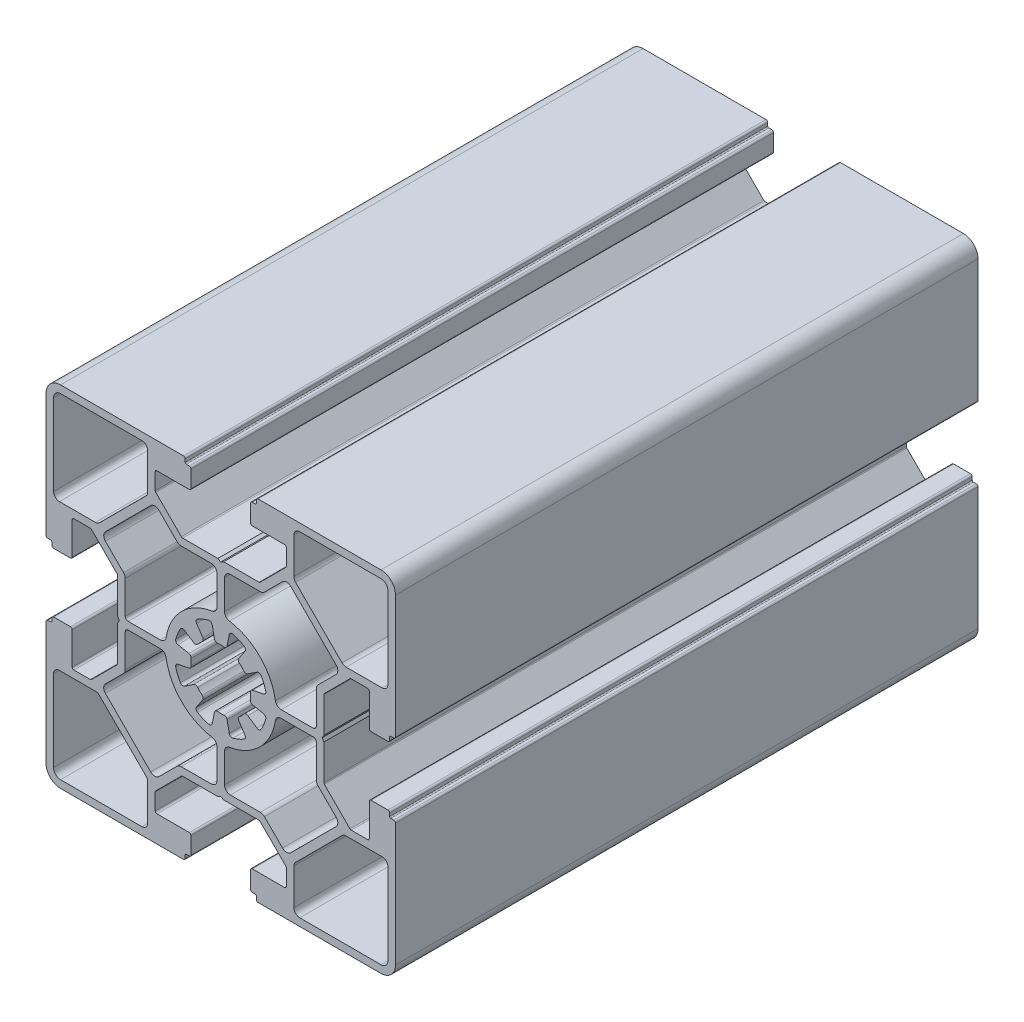
SolidWorks part; units mm, degrees
ref_plane "前视基准面" through (0, 0, 0) normal (0, 0, 1) x (1, 0, 0)
ref_plane "上视基准面" through (0, 0, 0) normal (0, 1, 0) x (1, 0, 0)
ref_plane "右视基准面" through (0, 0, 0) normal (1, 0, 0) x (0, 0, -1)
sketch "草图1" plane through (0, 0, 0) normal (0, 0, 1) x (1, 0, 0)
  line B0 (17.7, -0.4992) -> (17.4113, 0.0008)
  line B1 (17.4113, 0.0008) -> (17.7, 0.5008)
  line B2 (17.7, 0.5008) -> (17.7, 6.5449)
  line B3 (17.7879, 6.757) -> (22.193, 11.1621)
  line B4 (22.4051, 11.25) -> (25.2, 11.25)
  line B5 (25.5, 10.95) -> (25.5, 5.4)
  line B6 (25.8, 5.1) -> (28.7, 5.1)
  line B7 (29, 5.4) -> (29, 5.9)
  line B8 (29.2, 6.1) -> (29.7, 6.1)
  line B9 (30, 6.4) -> (30, 27.5)
  line B10 (27.5, 30) -> (6.4, 30)
  line B11 (6.1, 29.7) -> (6.1, 29.2)
  line B12 (5.9, 29) -> (5.4, 29)
  line B13 (5.1, 28.7) -> (5.1, 25.8)
  line B14 (5.4, 25.5) -> (10.95, 25.5)
  line B15 (11.25, 25.2) -> (11.25, 22.4051)
  line B16 (11.1621, 22.193) -> (6.757, 17.7879)
  line B17 (6.5449, 17.7) -> (0.5, 17.7)
  line B18 (0.5, 17.7) -> (0, 17.4113)
  line B19 (0, 17.4113) -> (-0.5, 17.7)
  line B20 (-0.5, 17.7) -> (-6.5449, 17.7)
  line B21 (-6.757, 17.7879) -> (-11.1621, 22.193)
  line B22 (-11.25, 22.4051) -> (-11.25, 25.2)
  line B23 (-10.95, 25.5) -> (-5.4, 25.5)
  line B24 (-5.1, 25.8) -> (-5.1, 28.7)
  line B25 (-5.4, 29) -> (-5.9, 29)
  line B26 (-6.1, 29.2) -> (-6.1, 29.7)
  line B27 (-6.4, 30) -> (-27.5, 30)
  line B28 (-30, 27.5) -> (-30, 6.4)
  line B29 (-29.7, 6.1) -> (-29.2, 6.1)
  line B30 (-29, 5.9) -> (-29, 5.4)
  line B31 (-28.7, 5.1) -> (-25.8, 5.1)
  line B32 (-25.5, 5.4) -> (-25.5, 10.95)
  line B33 (-25.2, 11.25) -> (-22.4051, 11.25)
  line B34 (-22.193, 11.1621) -> (-17.7879, 6.757)
  line B35 (-17.7, 6.5449) -> (-17.7, 0.5008)
  line B36 (-17.7, 0.5008) -> (-17.4113, 0.0008)
  line B37 (-17.4113, 0.0008) -> (-17.7, -0.4992)
  line B38 (-17.7, -0.4992) -> (-17.7, -6.5449)
  line B39 (-17.7879, -6.757) -> (-22.193, -11.1621)
  line B40 (-22.4051, -11.25) -> (-25.2, -11.25)
  line B41 (-25.5, -10.95) -> (-25.5, -5.4)
  line B42 (-25.8, -5.1) -> (-28.7, -5.1)
  line B43 (-29, -5.4) -> (-29, -5.9)
  line B44 (-29.2, -6.1) -> (-29.7, -6.1)
  line B45 (-30, -6.4) -> (-30, -27.5)
  line B46 (-27.5, -30) -> (-6.4, -30)
  line B47 (-6.1, -29.7) -> (-6.1, -29.2)
  line B48 (-5.9, -29) -> (-5.4, -29)
  line B49 (-5.1, -28.7) -> (-5.1, -25.8)
  line B50 (-5.4, -25.5) -> (-10.95, -25.5)
  line B51 (-11.25, -25.2) -> (-11.25, -22.4051)
  line B52 (-11.1621, -22.193) -> (-6.757, -17.7879)
  line B53 (-6.5449, -17.7) -> (-0.5, -17.7)
  line B54 (-0.5, -17.7) -> (0, -17.4113)
  line B55 (0, -17.4113) -> (0.5, -17.7)
  line B56 (0.5, -17.7) -> (6.5449, -17.7)
  line B57 (6.757, -17.7879) -> (11.1621, -22.193)
  line B58 (11.25, -22.4051) -> (11.25, -25.2)
  line B59 (10.95, -25.5) -> (5.4, -25.5)
  line B60 (5.1, -25.8) -> (5.1, -28.7)
  line B61 (5.4, -29) -> (5.9, -29)
  line B62 (6.1, -29.2) -> (6.1, -29.7)
  line B63 (6.4, -30) -> (27.5, -30)
  line B64 (30, -27.5) -> (30, -6.4)
  line B65 (29.7, -6.1) -> (29.2, -6.1)
  line B66 (29, -5.9) -> (29, -5.4)
  line B67 (28.7, -5.1) -> (25.8, -5.1)
  line B68 (25.5, -5.4) -> (25.5, -10.95)
  line B69 (25.2, -11.25) -> (22.4051, -11.25)
  line B70 (22.193, -11.1621) -> (17.7879, -6.757)
  line B71 (17.7, -6.5449) -> (17.7, -0.4992)
  line B72 (-16.4, 1.15) -> (-16.4, 6.7934)
  line B73 (-16.6929, 7.5005) -> (-19.799, 10.6066)
  line B74 (-19.799, 12.0208) -> (-12.0208, 19.799)
  line B75 (-10.6066, 19.799) -> (-7.5005, 16.6929)
  line B76 (-6.7934, 16.4) -> (-1.65, 16.4)
  line B77 (-0.65, 15.4) -> (-0.65, 10.3695)
  line B78 (-10.3695, 0.65) -> (-15.9, 0.65)
  line B79 (21.5225, 12.55) -> (27.7, 12.55)
  line B80 (28.7, 13.55) -> (28.7, 27.5)
  line B81 (27.5, 28.7) -> (13.55, 28.7)
  line B82 (12.55, 27.7) -> (12.55, 21.5225)
  line B83 (12.8429, 20.8154) -> (20.8154, 12.8429)
  line B84 (16.4, 6.7934) -> (16.4, 1.15)
  line B85 (15.9, 0.65) -> (10.3695, 0.65)
  line B86 (0.65, 10.3695) -> (0.65, 15.4)
  line B87 (1.65, 16.4) -> (6.7934, 16.4)
  line B88 (7.5005, 16.6929) -> (10.6066, 19.799)
  line B89 (12.0208, 19.799) -> (19.799, 12.0208)
  line B90 (19.799, 10.6066) -> (16.6929, 7.5005)
  line B91 (16.4, -1.15) -> (16.4, -6.7934)
  line B92 (16.6929, -7.5005) -> (19.799, -10.6066)
  line B93 (19.799, -12.0208) -> (12.0208, -19.799)
  line B94 (10.6066, -19.799) -> (7.5005, -16.6929)
  line B95 (6.7934, -16.4) -> (1.65, -16.4)
  line B96 (0.65, -15.4) -> (0.65, -10.3695)
  line B97 (10.3695, -0.65) -> (15.9, -0.65)
  line B98 (4.1575, -6.2221) -> (3.0988, -4.6376)
  line B99 (4.6376, -3.0988) -> (6.2221, -4.1575)
  line B100 (7.3395, -1.4599) -> (5.4705, -1.0881)
  line B101 (5.4705, 1.0881) -> (7.3395, 1.4599)
  line B102 (6.2221, 4.1575) -> (4.6376, 3.0988)
  line B103 (3.0988, 4.6376) -> (4.1575, 6.2221)
  line B104 (1.4599, 7.3395) -> (1.0881, 5.4705)
  line B105 (-1.0881, 5.4705) -> (-1.4599, 7.3395)
  line B106 (-4.1575, 6.2221) -> (-3.0988, 4.6376)
  line B107 (-4.6376, 3.0988) -> (-6.2221, 4.1575)
  line B108 (-7.3395, 1.4599) -> (-5.4705, 1.0881)
  line B109 (-5.4705, -1.0881) -> (-7.3395, -1.4599)
  line B110 (-6.2221, -4.1575) -> (-4.6376, -3.0988)
  line B111 (-3.0988, -4.6376) -> (-4.1575, -6.2221)
  line B112 (-1.4599, -7.3395) -> (-1.0881, -5.4705)
  line B113 (1.0881, -5.4705) -> (1.4599, -7.3395)
  line B114 (-21.5225, -12.55) -> (-27.7, -12.55)
  line B115 (-28.7, -13.55) -> (-28.7, -27.5)
  line B116 (-27.5, -28.7) -> (-13.55, -28.7)
  line B117 (-12.55, -27.7) -> (-12.55, -21.5225)
  line B118 (-12.8429, -20.8154) -> (-20.8154, -12.8429)
  line B119 (-16.4, -6.7934) -> (-16.4, -1.15)
  line B120 (-15.9, -0.65) -> (-10.3695, -0.65)
  line B121 (-0.65, -10.3695) -> (-0.65, -15.4)
  line B122 (-1.65, -16.4) -> (-6.7934, -16.4)
  line B123 (-7.5005, -16.6929) -> (-10.6066, -19.799)
  line B124 (-12.0208, -19.799) -> (-19.799, -12.0208)
  line B125 (-19.799, -10.6066) -> (-16.6929, -7.5005)
  line B126 (-20.8154, 12.8429) -> (-12.8429, 20.8154)
  line B127 (-12.55, 21.5225) -> (-12.55, 27.7)
  line B128 (-13.55, 28.7) -> (-27.5, 28.7)
  line B129 (-28.7, 27.5) -> (-28.7, 13.55)
  line B130 (-27.7, 12.55) -> (-21.5225, 12.55)
  line B131 (20.8154, -12.8429) -> (12.8429, -20.8154)
  line B132 (12.55, -21.5225) -> (12.55, -27.7)
  line B133 (13.55, -28.7) -> (27.5, -28.7)
  line B134 (28.7, -27.5) -> (28.7, -13.55)
  line B135 (27.7, -12.55) -> (21.5225, -12.55)
  arc B136 (17.7879, 6.757) -> (17.7, 6.5449) centre (18, 6.5449) ccw
  arc B137 (22.4051, 11.25) -> (22.193, 11.1621) centre (22.4051, 10.95) ccw
  arc B138 (25.5, 10.95) -> (25.2, 11.25) centre (25.2, 10.95) ccw
  arc B139 (25.5, 5.4) -> (25.8, 5.1) centre (25.8, 5.4) ccw
  arc B140 (28.7, 5.1) -> (29, 5.4) centre (28.7, 5.4) ccw
  arc B141 (29.2, 6.1) -> (29, 5.9) centre (29.2, 5.9) ccw
  arc B142 (29.7, 6.1) -> (30, 6.4) centre (29.7, 6.4) ccw
  arc B143 (30, 27.5) -> (27.5, 30) centre (27.5, 27.5) ccw
  arc B144 (6.4, 30) -> (6.1, 29.7) centre (6.4, 29.7) ccw
  arc B145 (5.9, 29) -> (6.1, 29.2) centre (5.9, 29.2) ccw
  arc B146 (5.4, 29) -> (5.1, 28.7) centre (5.4, 28.7) ccw
  arc B147 (5.1, 25.8) -> (5.4, 25.5) centre (5.4, 25.8) ccw
  arc B148 (11.25, 25.2) -> (10.95, 25.5) centre (10.95, 25.2) ccw
  arc B149 (11.1621, 22.193) -> (11.25, 22.4051) centre (10.95, 22.4051) ccw
  arc B150 (6.5449, 17.7) -> (6.757, 17.7879) centre (6.5449, 18) ccw
  arc B151 (-6.757, 17.7879) -> (-6.5449, 17.7) centre (-6.5449, 18) ccw
  arc B152 (-11.25, 22.4051) -> (-11.1621, 22.193) centre (-10.95, 22.4051) ccw
  arc B153 (-10.95, 25.5) -> (-11.25, 25.2) centre (-10.95, 25.2) ccw
  arc B154 (-5.4, 25.5) -> (-5.1, 25.8) centre (-5.4, 25.8) ccw
  arc B155 (-5.1, 28.7) -> (-5.4, 29) centre (-5.4, 28.7) ccw
  arc B156 (-6.1, 29.2) -> (-5.9, 29) centre (-5.9, 29.2) ccw
  arc B157 (-6.1, 29.7) -> (-6.4, 30) centre (-6.4, 29.7) ccw
  arc B158 (-27.5, 30) -> (-30, 27.5) centre (-27.5, 27.5) ccw
  arc B159 (-30, 6.4) -> (-29.7, 6.1) centre (-29.7, 6.4) ccw
  arc B160 (-29, 5.9) -> (-29.2, 6.1) centre (-29.2, 5.9) ccw
  arc B161 (-29, 5.4) -> (-28.7, 5.1) centre (-28.7, 5.4) ccw
  arc B162 (-25.8, 5.1) -> (-25.5, 5.4) centre (-25.8, 5.4) ccw
  arc B163 (-25.2, 11.25) -> (-25.5, 10.95) centre (-25.2, 10.95) ccw
  arc B164 (-22.193, 11.1621) -> (-22.4051, 11.25) centre (-22.4051, 10.95) ccw
  arc B165 (-17.7, 6.5449) -> (-17.7879, 6.757) centre (-18, 6.5449) ccw
  arc B166 (-17.7879, -6.757) -> (-17.7, -6.5449) centre (-18, -6.5449) ccw
  arc B167 (-22.4051, -11.25) -> (-22.193, -11.1621) centre (-22.4051, -10.95) ccw
  arc B168 (-25.5, -10.95) -> (-25.2, -11.25) centre (-25.2, -10.95) ccw
  arc B169 (-25.5, -5.4) -> (-25.8, -5.1) centre (-25.8, -5.4) ccw
  arc B170 (-28.7, -5.1) -> (-29, -5.4) centre (-28.7, -5.4) ccw
  arc B171 (-29.2, -6.1) -> (-29, -5.9) centre (-29.2, -5.9) ccw
  arc B172 (-29.7, -6.1) -> (-30, -6.4) centre (-29.7, -6.4) ccw
  arc B173 (-30, -27.5) -> (-27.5, -30) centre (-27.5, -27.5) ccw
  arc B174 (-6.4, -30) -> (-6.1, -29.7) centre (-6.4, -29.7) ccw
  arc B175 (-5.9, -29) -> (-6.1, -29.2) centre (-5.9, -29.2) ccw
  arc B176 (-5.4, -29) -> (-5.1, -28.7) centre (-5.4, -28.7) ccw
  arc B177 (-5.1, -25.8) -> (-5.4, -25.5) centre (-5.4, -25.8) ccw
  arc B178 (-11.25, -25.2) -> (-10.95, -25.5) centre (-10.95, -25.2) ccw
  arc B179 (-11.1621, -22.193) -> (-11.25, -22.4051) centre (-10.95, -22.4051) ccw
  arc B180 (-6.5449, -17.7) -> (-6.757, -17.7879) centre (-6.5449, -18) ccw
  arc B181 (6.757, -17.7879) -> (6.5449, -17.7) centre (6.5449, -18) ccw
  arc B182 (11.25, -22.4051) -> (11.1621, -22.193) centre (10.95, -22.4051) ccw
  arc B183 (10.95, -25.5) -> (11.25, -25.2) centre (10.95, -25.2) ccw
  arc B184 (5.4, -25.5) -> (5.1, -25.8) centre (5.4, -25.8) ccw
  arc B185 (5.1, -28.7) -> (5.4, -29) centre (5.4, -28.7) ccw
  arc B186 (6.1, -29.2) -> (5.9, -29) centre (5.9, -29.2) ccw
  arc B187 (6.1, -29.7) -> (6.4, -30) centre (6.4, -29.7) ccw
  arc B188 (27.5, -30) -> (30, -27.5) centre (27.5, -27.5) ccw
  arc B189 (30, -6.4) -> (29.7, -6.1) centre (29.7, -6.4) ccw
  arc B190 (29, -5.9) -> (29.2, -6.1) centre (29.2, -5.9) ccw
  arc B191 (29, -5.4) -> (28.7, -5.1) centre (28.7, -5.4) ccw
  arc B192 (25.8, -5.1) -> (25.5, -5.4) centre (25.8, -5.4) ccw
  arc B193 (25.2, -11.25) -> (25.5, -10.95) centre (25.2, -10.95) ccw
  arc B194 (22.193, -11.1621) -> (22.4051, -11.25) centre (22.4051, -10.95) ccw
  arc B195 (17.7, -6.5449) -> (17.7879, -6.757) centre (18, -6.5449) ccw
  arc B196 (-16.4, 6.7934) -> (-16.6929, 7.5005) centre (-17.4, 6.7934) ccw
  arc B197 (-19.799, 12.0208) -> (-19.799, 10.6066) centre (-19.0919, 11.3137) ccw
  arc B198 (-10.6066, 19.799) -> (-12.0208, 19.799) centre (-11.3137, 19.0919) ccw
  arc B199 (-7.5005, 16.6929) -> (-6.7934, 16.4) centre (-6.7934, 17.4) ccw
  arc B200 (-0.65, 15.4) -> (-1.65, 16.4) centre (-1.65, 15.4) ccw
  arc B201 (-1.4929, 9.382) -> (-0.65, 10.3695) centre (-1.65, 10.3695) ccw
  arc B202 (-1.4929, 9.382) -> (-9.382, 1.4929) centre (0, 0) ccw
  arc B203 (-10.3695, 0.65) -> (-9.382, 1.4929) centre (-10.3695, 1.65) ccw
  arc B204 (-16.4, 1.15) -> (-15.9, 0.65) centre (-15.9, 1.15) ccw
  arc B205 (20.8154, 12.8429) -> (21.5225, 12.55) centre (21.5225, 13.55) ccw
  arc B206 (27.7, 12.55) -> (28.7, 13.55) centre (27.7, 13.55) ccw
  arc B207 (28.7, 27.5) -> (27.5, 28.7) centre (27.5, 27.5) ccw
  arc B208 (13.55, 28.7) -> (12.55, 27.7) centre (13.55, 27.7) ccw
  arc B209 (12.55, 21.5225) -> (12.8429, 20.8154) centre (13.55, 21.5225) ccw
  arc B210 (15.9, 0.65) -> (16.4, 1.15) centre (15.9, 1.15) ccw
  arc B211 (9.382, 1.4929) -> (10.3695, 0.65) centre (10.3695, 1.65) ccw
  arc B212 (9.382, 1.4929) -> (1.4929, 9.382) centre (0, 0) ccw
  arc B213 (0.65, 10.3695) -> (1.4929, 9.382) centre (1.65, 10.3695) ccw
  arc B214 (1.65, 16.4) -> (0.65, 15.4) centre (1.65, 15.4) ccw
  arc B215 (6.7934, 16.4) -> (7.5005, 16.6929) centre (6.7934, 17.4) ccw
  arc B216 (12.0208, 19.799) -> (10.6066, 19.799) centre (11.3137, 19.0919) ccw
  arc B217 (19.799, 10.6066) -> (19.799, 12.0208) centre (19.0919, 11.3137) ccw
  arc B218 (16.6929, 7.5005) -> (16.4, 6.7934) centre (17.4, 6.7934) ccw
  arc B219 (16.4, -6.7934) -> (16.6929, -7.5005) centre (17.4, -6.7934) ccw
  arc B220 (19.799, -12.0208) -> (19.799, -10.6066) centre (19.0919, -11.3137) ccw
  arc B221 (10.6066, -19.799) -> (12.0208, -19.799) centre (11.3137, -19.0919) ccw
  arc B222 (7.5005, -16.6929) -> (6.7934, -16.4) centre (6.7934, -17.4) ccw
  arc B223 (0.65, -15.4) -> (1.65, -16.4) centre (1.65, -15.4) ccw
  arc B224 (1.4929, -9.382) -> (0.65, -10.3695) centre (1.65, -10.3695) ccw
  arc B225 (1.4929, -9.382) -> (9.382, -1.4929) centre (0, 0) ccw
  arc B226 (10.3695, -0.65) -> (9.382, -1.4929) centre (10.3695, -1.65) ccw
  arc B227 (16.4, -1.15) -> (15.9, -0.65) centre (15.9, -1.15) ccw
  arc B228 (2.0803, -7.7248) -> (3.9912, -6.9333) centre (0, 0) ccw
  arc B229 (3.9912, -6.9333) -> (4.1575, -6.2221) centre (3.7418, -6.4999) ccw
  arc B230 (3.2007, -3.9706) -> (3.0988, -4.6376) centre (3.5145, -4.3598) ccw
  arc B231 (3.2007, -3.9706) -> (3.9706, -3.2007) centre (0, 0) ccw
  arc B232 (4.6376, -3.0988) -> (3.9706, -3.2007) centre (4.3598, -3.5145) ccw
  arc B233 (6.2221, -4.1575) -> (6.9333, -3.9912) centre (6.4999, -3.7418) ccw
  arc B234 (6.9333, -3.9912) -> (7.7248, -2.0803) centre (0, 0) ccw
  arc B235 (7.7248, -2.0803) -> (7.3395, -1.4599) centre (7.242, -1.9503) ccw
  arc B236 (5.0709, -0.5444) -> (5.4705, -1.0881) centre (5.568, -0.5977) ccw
  arc B237 (5.0709, -0.5444) -> (5.0709, 0.5444) centre (0, 0) ccw
  arc B238 (5.4705, 1.0881) -> (5.0709, 0.5444) centre (5.568, 0.5977) ccw
  arc B239 (7.3395, 1.4599) -> (7.7248, 2.0803) centre (7.242, 1.9503) ccw
  arc B240 (7.7248, 2.0803) -> (6.9333, 3.9912) centre (0, 0) ccw
  arc B241 (6.9333, 3.9912) -> (6.2221, 4.1575) centre (6.4999, 3.7418) ccw
  arc B242 (3.9706, 3.2007) -> (4.6376, 3.0988) centre (4.3598, 3.5145) ccw
  arc B243 (3.9706, 3.2007) -> (3.2007, 3.9706) centre (0, 0) ccw
  arc B244 (3.0988, 4.6376) -> (3.2007, 3.9706) centre (3.5145, 4.3598) ccw
  arc B245 (4.1575, 6.2221) -> (3.9912, 6.9333) centre (3.7418, 6.4999) ccw
  arc B246 (3.9912, 6.9333) -> (2.0803, 7.7248) centre (0, 0) ccw
  arc B247 (2.0803, 7.7248) -> (1.4599, 7.3395) centre (1.9503, 7.242) ccw
  arc B248 (0.5444, 5.0709) -> (1.0881, 5.4705) centre (0.5977, 5.568) ccw
  arc B249 (0.5444, 5.0709) -> (-0.5444, 5.0709) centre (0, 0) ccw
  arc B250 (-1.0881, 5.4705) -> (-0.5444, 5.0709) centre (-0.5977, 5.568) ccw
  arc B251 (-1.4599, 7.3395) -> (-2.0803, 7.7248) centre (-1.9503, 7.242) ccw
  arc B252 (-2.0803, 7.7248) -> (-3.9912, 6.9333) centre (0, 0) ccw
  arc B253 (-3.9912, 6.9333) -> (-4.1575, 6.2221) centre (-3.7418, 6.4999) ccw
  arc B254 (-3.2007, 3.9706) -> (-3.0988, 4.6376) centre (-3.5145, 4.3598) ccw
  arc B255 (-3.2007, 3.9706) -> (-3.9706, 3.2007) centre (0, 0) ccw
  arc B256 (-4.6376, 3.0988) -> (-3.9706, 3.2007) centre (-4.3598, 3.5145) ccw
  arc B257 (-6.2221, 4.1575) -> (-6.9333, 3.9912) centre (-6.4999, 3.7418) ccw
  arc B258 (-6.9333, 3.9912) -> (-7.7248, 2.0803) centre (0, 0) ccw
  arc B259 (-7.7248, 2.0803) -> (-7.3395, 1.4599) centre (-7.242, 1.9503) ccw
  arc B260 (-5.0709, 0.5444) -> (-5.4705, 1.0881) centre (-5.568, 0.5977) ccw
  arc B261 (-5.0709, 0.5444) -> (-5.0709, -0.5444) centre (0, 0) ccw
  arc B262 (-5.4705, -1.0881) -> (-5.0709, -0.5444) centre (-5.568, -0.5977) ccw
  arc B263 (-7.3395, -1.4599) -> (-7.7248, -2.0803) centre (-7.242, -1.9503) ccw
  arc B264 (-7.7248, -2.0803) -> (-6.9333, -3.9912) centre (0, 0) ccw
  arc B265 (-6.9333, -3.9912) -> (-6.2221, -4.1575) centre (-6.4999, -3.7418) ccw
  arc B266 (-3.9706, -3.2007) -> (-4.6376, -3.0988) centre (-4.3598, -3.5145) ccw
  arc B267 (-3.9706, -3.2007) -> (-3.2007, -3.9706) centre (0, 0) ccw
  arc B268 (-3.0988, -4.6376) -> (-3.2007, -3.9706) centre (-3.5145, -4.3598) ccw
  arc B269 (-4.1575, -6.2221) -> (-3.9912, -6.9333) centre (-3.7418, -6.4999) ccw
  arc B270 (-3.9912, -6.9333) -> (-2.0803, -7.7248) centre (0, 0) ccw
  arc B271 (-2.0803, -7.7248) -> (-1.4599, -7.3395) centre (-1.9503, -7.242) ccw
  arc B272 (-0.5444, -5.0709) -> (-1.0881, -5.4705) centre (-0.5977, -5.568) ccw
  arc B273 (-0.5444, -5.0709) -> (0.5444, -5.0709) centre (0, 0) ccw
  arc B274 (1.0881, -5.4705) -> (0.5444, -5.0709) centre (0.5977, -5.568) ccw
  arc B275 (1.4599, -7.3395) -> (2.0803, -7.7248) centre (1.9503, -7.242) ccw
  arc B276 (-20.8154, -12.8429) -> (-21.5225, -12.55) centre (-21.5225, -13.55) ccw
  arc B277 (-27.7, -12.55) -> (-28.7, -13.55) centre (-27.7, -13.55) ccw
  arc B278 (-28.7, -27.5) -> (-27.5, -28.7) centre (-27.5, -27.5) ccw
  arc B279 (-13.55, -28.7) -> (-12.55, -27.7) centre (-13.55, -27.7) ccw
  arc B280 (-12.55, -21.5225) -> (-12.8429, -20.8154) centre (-13.55, -21.5225) ccw
  arc B281 (-15.9, -0.65) -> (-16.4, -1.15) centre (-15.9, -1.15) ccw
  arc B282 (-9.382, -1.4929) -> (-10.3695, -0.65) centre (-10.3695, -1.65) ccw
  arc B283 (-9.382, -1.4929) -> (-1.4929, -9.382) centre (0, 0) ccw
  arc B284 (-0.65, -10.3695) -> (-1.4929, -9.382) centre (-1.65, -10.3695) ccw
  arc B285 (-1.65, -16.4) -> (-0.65, -15.4) centre (-1.65, -15.4) ccw
  arc B286 (-6.7934, -16.4) -> (-7.5005, -16.6929) centre (-6.7934, -17.4) ccw
  arc B287 (-12.0208, -19.799) -> (-10.6066, -19.799) centre (-11.3137, -19.0919) ccw
  arc B288 (-19.799, -10.6066) -> (-19.799, -12.0208) centre (-19.0919, -11.3137) ccw
  arc B289 (-16.6929, -7.5005) -> (-16.4, -6.7934) centre (-17.4, -6.7934) ccw
  arc B290 (-21.5225, 12.55) -> (-20.8154, 12.8429) centre (-21.5225, 13.55) ccw
  arc B291 (-12.8429, 20.8154) -> (-12.55, 21.5225) centre (-13.55, 21.5225) ccw
  arc B292 (-12.55, 27.7) -> (-13.55, 28.7) centre (-13.55, 27.7) ccw
  arc B293 (-27.5, 28.7) -> (-28.7, 27.5) centre (-27.5, 27.5) ccw
  arc B294 (-28.7, 13.55) -> (-27.7, 12.55) centre (-27.7, 13.55) ccw
  arc B295 (21.5225, -12.55) -> (20.8154, -12.8429) centre (21.5225, -13.55) ccw
  arc B296 (12.8429, -20.8154) -> (12.55, -21.5225) centre (13.55, -21.5225) ccw
  arc B297 (12.55, -27.7) -> (13.55, -28.7) centre (13.55, -27.7) ccw
  arc B298 (27.5, -28.7) -> (28.7, -27.5) centre (27.5, -27.5) ccw
  arc B299 (28.7, -13.55) -> (27.7, -12.55) centre (27.7, -13.55) ccw
sketch_block_instance "A$C3E9B6BC0-1"
sketch_block "A$C3E9B6BC0"
extrude "凸台-拉伸1" add sketch "草图1" along normal blind 100
